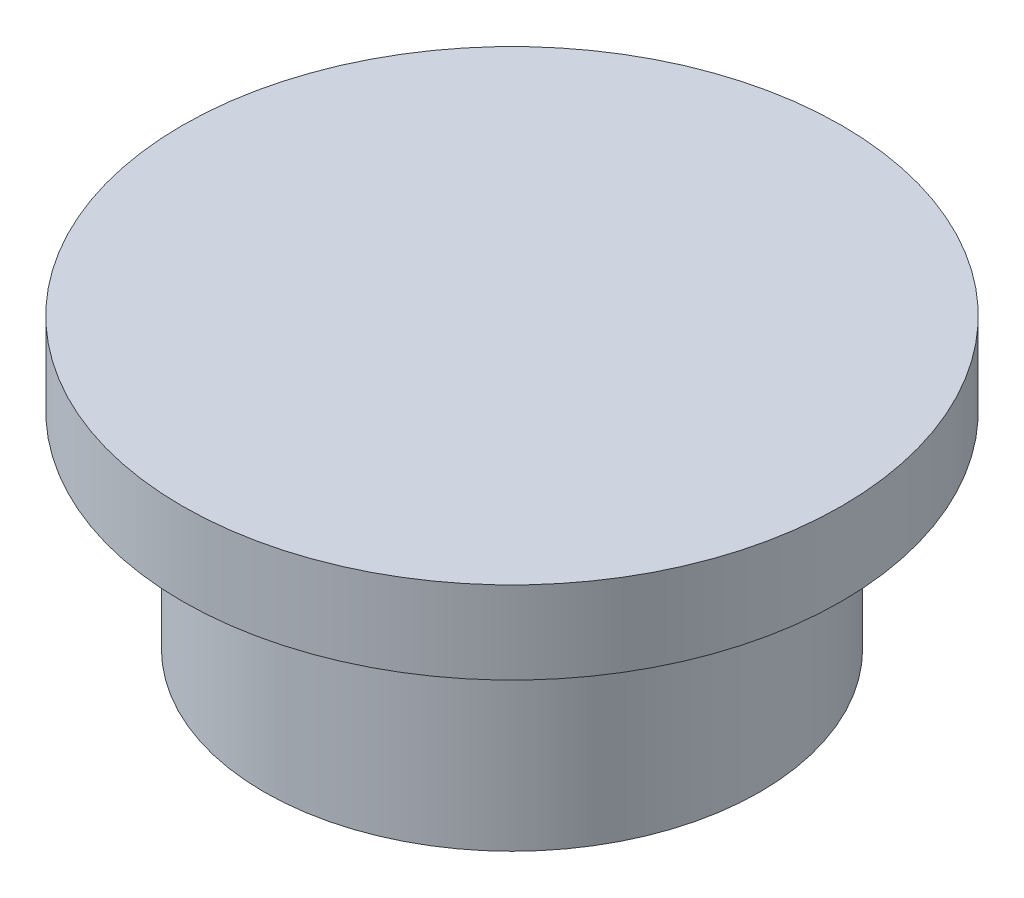
SolidWorks part; units mm, degrees
ref_plane "Front Plane" through (0, 0, 0) normal (0, 0, 1) x (1, 0, 0)
ref_plane "Top Plane" through (0, 0, 0) normal (0, 1, 0) x (1, 0, 0)
ref_plane "Right Plane" through (0, 0, 0) normal (1, 0, 0) x (0, 0, -1)
sketch "Sketch1" plane through (0, 0, 0) normal (0, 0, 1) x (1, 0, 0)
  line L0 (0, 1.4887) -> (0, 14.0727) construction
  line L7 (0, 0) -> (3.175, 0)
  line L8 (3.175, 0) -> (3.175, -0.7937)
  line L9 (3.175, -0.7937) -> (2.3876, -0.7938)
  line L10 (2.3876, -0.7938) -> (2.3876, -2.7781)
  line L11 (2.3876, -2.7781) -> (0, -2.7781)
  line L12 (0, 0) -> (0, -2.7781)
  dimension "D1" = 1.9844
  dimension "D2" = 0.7937
  dimension "D3" = 6.35
  dimension "D4" = 4.7752
revolve "Revolve1" add sketch "Sketch1" angle 360 about L0
